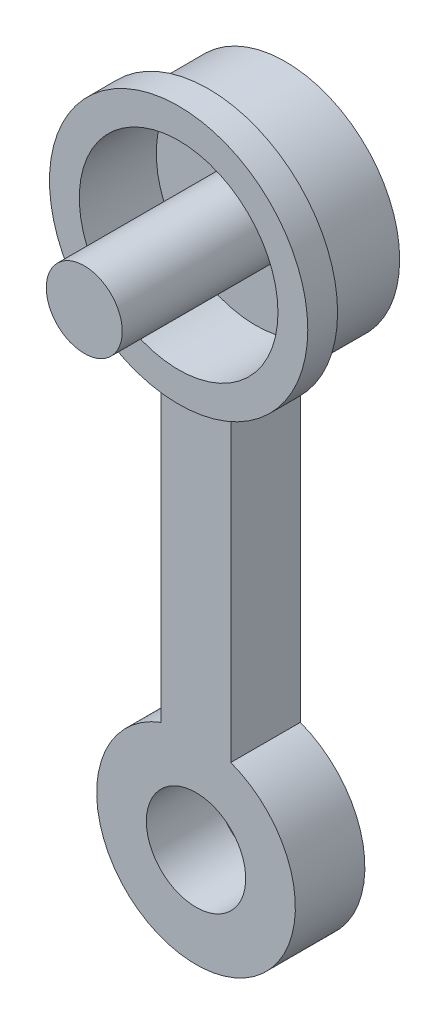
SolidWorks part; units mm, degrees
ref_plane "Alzado" through (0, 0, 0) normal (0, 0, 1) x (1, 0, 0)
ref_plane "Planta" through (0, 0, 0) normal (0, 1, 0) x (1, 0, 0)
ref_plane "Vista lateral" through (0, 0, 0) normal (1, 0, 0) x (0, 0, -1)
sketch "Croquis1" plane through (0, 0, 0) normal (0, 0, 1) x (1, 0, 0)
  circle A0 centre (0, 0) radius 10
  dimension "D1" = 20
extrude "Saliente-Extruir1" add sketch "Croquis1" along normal blind 3
sketch "Croquis2" plane through (0, 0, 3) normal (0, 0, 1) x (1, 0, 0)
  circle A0 centre (0, 0) radius 2.5
  circle A1 centre (0, 0) radius 4
  circle A2 centre (0, 0) radius 11.5
  circle A3 centre (0, 0) radius 10
  circle M1 centre (0, 0) radius 10
  dimension "D1" = 5
  dimension "D2" = 8
  dimension "D3" = 23
extrude "Saliente-Extruir3" add sketch "Croquis2" along normal blind 8 separate body contours A2 M1
sketch "Croquis3" plane through (0, 0, 3) normal (0, 0, -1) x (-1, 0, 0)
  circle A0 centre (0, 0) radius 11.5
  circle A1 centre (0, 0) radius 10
extrude "Saliente-Extruir4" add sketch "Croquis3" along normal up to surface (3 mm away) up to face at (10, 0, 0)
ref_plane "Plano1" through (0, 11.5, 0) normal (0, 1, 0) x (1, 0, 0)
sketch "Croquis7" plane through (0, 0, 11) normal (0, 0, 1) x (1, 0, 0)
  line L0 (0, 11.5) -> (0, 0) construction
  line L1 (6.05, 11.5) -> (-6.05, 11.5) construction
  line L2 (0, 0) -> (11.5, 0) construction
  circle A0 centre (0, 0) radius 11.5 construction
ref_plane "Plano2" through (0, 11.5, 0) normal (0, 1, 0) x (1, 0, 0)
ref_plane "Plano3" through (0, 11.5, 0) normal (0, 1, 0) x (1, 0, 0)
sketch "Croquis9" plane through (0, 0, 11) normal (0, 0, 1) x (1, 0, 0)
  line L0 (11.5, 0) -> (11.5, 3)
  line L1 (11.5, 3) -> (12.0602, 3)
  line L2 (12.0602, 3) -> (12.0602, -3)
  line L3 (11.5, 0) -> (11.5, -3)
  line L4 (12.0602, -3) -> (11.5, -3)
  dimension "D1" = 3
  dimension "D2" = 3
extrude "Saliente-Extruir5" add sketch "Croquis9" against normal blind 8 separate body
sketch "Croquis11" plane through (0, 0, 11) normal (0, 0, 1) x (1, 0, 0)
  line L1 (11.5, 3) -> (12.0602, 3)
  line L2 (11.5, 3) -> (11.5, -3)
  line L3 (11.5, -3) -> (12.0602, -3)
  line L4 (12.0602, 3) -> (12.0602, -3)
extrude "Cortar-Extruir3" cut sketch "Croquis11" against normal blind 8
ref_plane "Plano4" through (-11.5, 0, 0) normal (-1, 0, 0) x (0, 0, 1)
sketch "Croquis12" plane through (0, 0, 3) normal (0, 0, 1) x (1, 0, 0)
  line L0 (0, 0) -> (0, -11.5) construction
  line L1 (0, -11.5) -> (-2.5, -11.5)
  line L2 (0, -11.5) -> (2.5, -11.5)
  line L3 (-2.5, -11.5) -> (-2.5, -10.878)
  line L4 (-2.5, -11.5) -> (2.5, -11.5)
  line L5 (-2.5, -11.5) -> (-2.5, -61.5)
  line L6 (-2.5, -61.5) -> (2.5, -61.5)
  line L7 (2.5, -11.5) -> (2.5, -61.5)
  line L8 (-2.5, -10.878) -> (0, -10.878)
  line L9 (0, -10.878) -> (0, -11.5)
  line L10 (0, -10.878) -> (2.5, -10.878)
  line L11 (2.5, -10.878) -> (2.5, -11.5)
  circle A0 centre (0, 0) radius 11.5 construction
  dimension "D1" = 2.5
  dimension "D2" = 2.5
  dimension "D3" = 50
extrude "Saliente-Extruir6" add sketch "Croquis12" against normal up to surface (3 mm away) contours L9 L8 L3 L1 | L11 L10 L9 L2 | L7 L2 L1 L5 L6 up to face at (11.5, 0, 0)
sketch "Croquis13" plane through (0, 0, 3) normal (0, 0, 1) x (1, 0, 0)
  line L1 (-2.5, -11.225) -> (2.5, -11.225)
  line L2 (-2.5, -11.225) -> (-2.5, -61.5)
  line L3 (-2.5, -61.5) -> (2.5, -61.5)
  line L4 (2.5, -11.225) -> (2.5, -61.5)
extrude "Saliente-Extruir7" add sketch "Croquis13" along normal up to surface (8 mm away) up to face at (10, 0, 11)
sketch "Croquis15" plane through (2.5, 0, 0) normal (1, 0, 0) x (0, 0, -1)
  line L0 (0, -11.225) -> (-11, -11.225) construction
  line L1 (-11, -61.5) -> (-9, -61.5)
  line L2 (-11, -61.5) -> (-11, -11.225)
  line L3 (-11, -11.225) -> (-9, -11.225)
  line L4 (-9, -61.5) -> (-9, -11.225)
  line L6 (0, -61.5) -> (-2, -61.5)
  line L7 (0, -61.5) -> (0, -11.225)
  line L8 (0, -11.225) -> (-2, -11.225)
  line L9 (-2, -61.5) -> (-2, -11.225)
  dimension "D1" = 2
  dimension "D2" = 2
extrude "Cortar-Extruir4" cut sketch "Croquis15" against normal blind 8
sketch "Croquis16" plane through (0, 0, 9) normal (0, 0, 1) x (1, 0, 0)
  line L0 (-2.5, -61.5) -> (-3.5, -61.5)
  line L1 (2.5, -61.5) -> (3.5, -61.5)
  line L2 (-3.5, -61.5) -> (-3.5, -10.233)
  line L3 (-3.5, -10.233) -> (3.5, -10.233)
  line L4 (3.5, -10.233) -> (3.5, -61.5)
  line L9 (-2.5, -61.5) -> (2.5, -61.5)
  line L10 (2.5, -61.5) -> (2.5, -11.225)
  line L11 (2.5, -11.225) -> (-2.5, -11.225)
  line L12 (-2.5, -11.225) -> (-2.5, -61.5)
  line L13 (-2.5, -61.5) -> (2.5, -61.5)
  dimension "D1" = 1
  dimension "D2" = 1
  dimension "D3" = 0
extrude "Saliente-Extruir8" add sketch "Croquis16" against normal up to surface (7 mm away) up to face at (0, -36.3625, 2)
sketch "Croquis21" plane through (0, 0, 2) normal (0, 0, -1) x (-1, 0, 0)
  line L0 (0, -11.225) -> (0, -52.725) construction
  line L1 (2.5, -11.225) -> (-2.5, -11.225) construction
  circle A0 centre (0, -52.725) radius 10
  dimension "D2" = 20
  dimension "D1" = 41.5
extrude "Saliente-Extruir9" add sketch "Croquis21" against normal up to surface (7 mm away) up to face at (0, -27.8969, 9)
sketch "Croquis22" plane through (0, 0, 2) normal (0, 0, -1) x (-1, 0, 0)
  circle A0 centre (0, -52.725) radius 5
  dimension "D1" = 10
extrude "Cortar-Extruir5" cut sketch "Croquis22" against normal blind 30
sketch "Croquis23" plane through (0, 0, 11) normal (0, 0, 1) x (1, 0, 0)
  line L0 (-2.5, -11.225) -> (2.5, -11.225) construction
  line L1 (-2.5, -11.225) -> (2.5, -11.225)
  arc A0 (2.5, -11.225) -> (-2.5, -11.225) centre (0, 0) ccw construction
  arc A1 (2.5, -11.225) -> (-2.5, -11.225) centre (0, 0) ccw
  circle A2 centre (0, 0) radius 10 construction
  circle A3 centre (0, 0) radius 10
extrude "Saliente-Extruir10" add sketch "Croquis23" along normal blind 1.25
sketch "Croquis24" plane through (0, 0, 12.25) normal (0, 0, 1) x (1, 0, 0)
  line L0 (-2.5, -11.225) -> (2.5, -11.225) construction
  line L1 (-2.5, -11.225) -> (2.5, -11.225)
  circle A0 centre (0, 0) radius 10 construction
  arc A1 (2.5, -11.225) -> (-2.5, -11.225) centre (0, 0) ccw construction
  circle A2 centre (0, 0) radius 10
  arc A3 (2.5, -11.225) -> (-2.5, -11.225) centre (0, 0) ccw
extrude "Cortar-Extruir6" cut sketch "Croquis24" against normal blind 1.5
sketch "Croquis25" plane through (0, 0, 10.75) normal (0, 0, 1) x (1, 0, 0)
  circle A0 centre (0, 0) radius 13
  arc A1 (2.5, -11.225) -> (-2.5, -11.225) centre (0, 0) ccw construction
  arc A2 (2.5, -11.225) -> (-2.5, -11.225) centre (0, 0) ccw
  arc M2 (2.5, -11.225) -> (-2.5, -11.225) centre (0, 0) ccw
  line M3 (-2.5, -11.225) -> (2.5, -11.225)
  dimension "D1" = 26
  dimension "D2" = 23
extrude "Saliente-Extruir11" add sketch "Croquis25" against normal blind 3 contours A0 M2 M3
sketch "Croquis30" plane through (0, 0, 3) normal (0, 0, 1) x (1, 0, 0)
  circle A0 centre (0, 0) radius 10
extrude "Cortar-Extruir14" cut sketch "Croquis30" against normal blind 10
sketch "Croquis31" plane through (0, 0, 0) normal (0, 0, -1) x (-1, 0, 0)
  circle A0 centre (0, 0) radius 11.5
  circle A1 centre (0, 0) radius 10 construction
  circle A2 centre (0, 0) radius 10
extrude "Saliente-Extruir12" add sketch "Croquis31" against normal up to surface (7.75 mm away) up to face at (0, 0.2564, 7.75)
sketch "Croquis32" plane through (0, 0, 0) normal (0, 0, -1) x (-1, 0, 0)
  circle A0 centre (0, 0) radius 10
extrude "Saliente-Extruir13" add sketch "Croquis32" against normal up to surface (10.75 mm away) up to face at (10, 0, 10.75)
sketch "Croquis33" plane through (0, 0, 0) normal (0, 0, -1) x (-1, 0, 0)
  circle A0 centre (0, 0) radius 11.5
sketch "Croquis34" plane through (0, 0, 10.75) normal (0, 0, 1) x (1, 0, 0)
  circle A0 centre (0, 0) radius 10
  dimension "D1" = 20
extrude "Cortar-Extruir15" cut sketch "Croquis34" against normal blind 7.75
sketch "Croquis36" plane through (0, 0, 3) normal (0, 0, 1) x (1, 0, 0)
  circle A0 centre (0, 0) radius 3.825
  dimension "D1" = 7.65
extrude "Saliente-Extruir14" add sketch "Croquis36" along normal up to surface (7.75 mm away) up to face at (10, 0, 10.75)
sketch "Croquis37" plane through (0, 0, 10.75) normal (0, 0, 1) x (1, 0, 0)
  circle A0 centre (0, 0) radius 3.825
extrude "Saliente-Extruir15" add sketch "Croquis37" along normal blind 9.5
